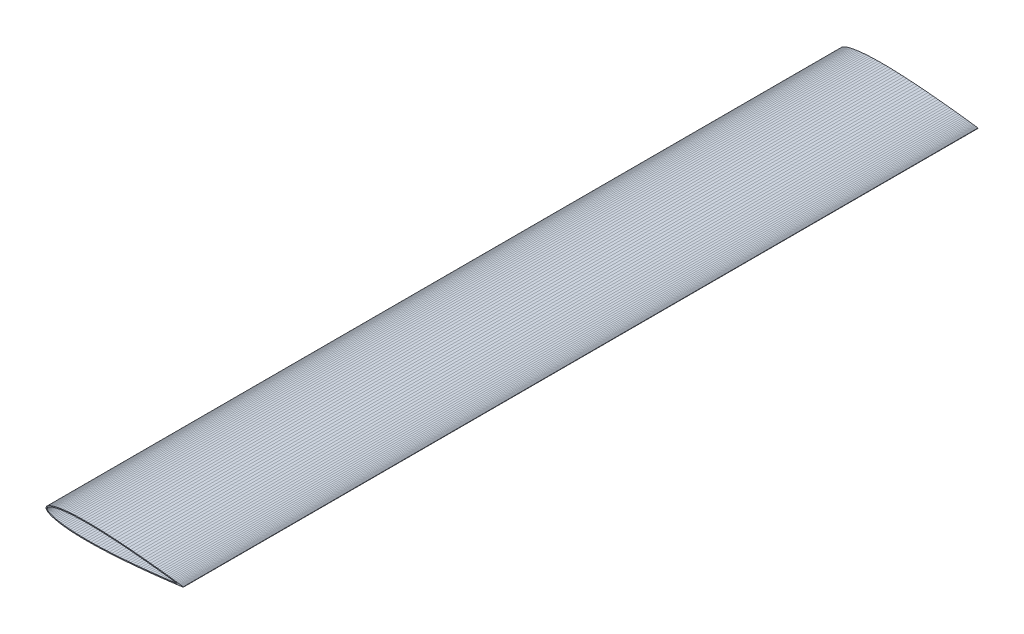
SolidWorks part; units mm, degrees
ref_plane "Front Plane" through (0, 0, 0) normal (0, 0, 1) x (1, 0, 0)
ref_plane "Top Plane" through (0, 0, 0) normal (0, 1, 0) x (1, 0, 0)
ref_plane "Right Plane" through (0, 0, 0) normal (1, 0, 0) x (0, 0, -1)
sketch "Sketch1" plane through (0, 0, 0) normal (0, 0, 1) x (1, 0, 0)
  line L0 (0.0146, 0.1318) -> (0.0586, 0.2613)
  line L1 (0.0586, 0.2613) -> (0.1317, 0.3885)
  line L2 (0.1317, 0.3885) -> (0.2339, 0.5131)
  line L3 (0.2339, 0.5131) -> (0.3651, 0.6352)
  line L4 (0.3651, 0.6352) -> (0.525, 0.7544)
  line L5 (0.525, 0.7544) -> (0.7134, 0.8708)
  line L6 (0.7134, 0.8708) -> (0.9299, 0.9839)
  line L7 (0.9299, 0.9839) -> (1.1744, 1.0938)
  line L8 (1.1744, 1.0938) -> (1.4463, 1.2)
  line L9 (1.4463, 1.2) -> (1.7453, 1.3025)
  line L10 (1.7453, 1.3025) -> (2.0709, 1.4009)
  line L11 (2.0709, 1.4009) -> (2.4226, 1.4951)
  line L12 (2.4226, 1.4951) -> (2.7998, 1.5848)
  line L13 (2.7998, 1.5848) -> (3.2021, 1.6698)
  line L14 (3.2021, 1.6698) -> (3.6287, 1.7499)
  line L15 (3.6287, 1.7499) -> (4.079, 1.8248)
  line L16 (4.079, 1.8248) -> (4.5523, 1.8944)
  line L17 (4.5523, 1.8944) -> (5.0479, 1.9586)
  line L18 (5.0479, 1.9586) -> (5.565, 2.0172)
  line L19 (5.565, 2.0172) -> (6.1028, 2.07)
  line L20 (6.1028, 2.07) -> (6.6605, 2.1169)
  line L21 (6.6605, 2.1169) -> (7.2372, 2.158)
  line L22 (7.2372, 2.158) -> (7.8321, 2.1931)
  line L23 (7.8321, 2.1931) -> (8.4442, 2.2223)
  line L24 (8.4442, 2.2223) -> (9.0725, 2.2455)
  line L25 (9.0725, 2.2455) -> (9.7162, 2.2628)
  line L26 (9.7162, 2.2628) -> (10.3742, 2.2742)
  line L27 (10.3742, 2.2742) -> (11.0455, 2.2799)
  line L28 (11.0455, 2.2799) -> (11.729, 2.28)
  line L29 (11.729, 2.28) -> (12.4238, 2.2746)
  line L30 (12.4238, 2.2746) -> (13.1287, 2.2638)
  line L31 (13.1287, 2.2638) -> (13.8426, 2.248)
  line L32 (13.8426, 2.248) -> (14.5645, 2.2272)
  line L33 (14.5645, 2.2272) -> (15.2933, 2.2016)
  line L34 (15.2933, 2.2016) -> (16.0277, 2.1716)
  line L35 (16.0277, 2.1716) -> (16.7668, 2.1374)
  line L36 (16.7668, 2.1374) -> (17.5093, 2.0991)
  line L37 (17.5093, 2.0991) -> (18.2541, 2.0572)
  line L38 (18.2541, 2.0572) -> (19, 2.0117)
  line L39 (19, 2.0117) -> (19.7459, 1.9631)
  line L40 (19.7459, 1.9631) -> (20.4907, 1.9115)
  line L41 (20.4907, 1.9115) -> (21.2332, 1.8572)
  line L42 (21.2332, 1.8572) -> (21.9723, 1.8006)
  line L43 (21.9723, 1.8006) -> (22.7067, 1.7417)
  line L44 (22.7067, 1.7417) -> (23.4355, 1.681)
  line L45 (23.4355, 1.681) -> (24.1574, 1.6186)
  line L46 (24.1574, 1.6186) -> (24.8713, 1.5549)
  line L47 (24.8713, 1.5549) -> (25.5762, 1.4899)
  line L48 (25.5762, 1.4899) -> (26.271, 1.4241)
  line L49 (26.271, 1.4241) -> (26.9545, 1.3576)
  line L50 (26.9545, 1.3576) -> (27.6258, 1.2906)
  line L51 (27.6258, 1.2906) -> (28.2838, 1.2233)
  line L52 (28.2838, 1.2233) -> (28.9275, 1.1561)
  line L53 (28.9275, 1.1561) -> (29.5558, 1.089)
  line L54 (29.5558, 1.089) -> (30.1679, 1.0224)
  line L55 (30.1679, 1.0224) -> (30.7628, 0.9564)
  line L56 (30.7628, 0.9564) -> (31.3395, 0.8912)
  line L57 (31.3395, 0.8912) -> (31.8972, 0.827)
  line L58 (31.8972, 0.827) -> (32.435, 0.7641)
  line L59 (32.435, 0.7641) -> (32.9521, 0.7026)
  line L60 (32.9521, 0.7026) -> (33.4477, 0.6427)
  line L61 (33.4477, 0.6427) -> (33.921, 0.5847)
  line L62 (33.921, 0.5847) -> (34.3713, 0.5287)
  line L63 (34.3713, 0.5287) -> (34.7979, 0.475)
  line L64 (34.7979, 0.475) -> (35.2002, 0.4237)
  line L65 (35.2002, 0.4237) -> (35.5774, 0.3749)
  line L66 (35.5774, 0.3749) -> (35.9291, 0.329)
  line L67 (35.9291, 0.329) -> (36.2547, 0.286)
  line L68 (36.2547, 0.286) -> (36.5537, 0.2462)
  line L69 (36.5537, 0.2462) -> (36.8256, 0.2096)
  line L70 (36.8256, 0.2096) -> (37.0701, 0.1764)
  line L71 (37.0701, 0.1764) -> (37.2866, 0.1468)
  line L72 (37.2866, 0.1468) -> (37.475, 0.1209)
  line L73 (37.475, 0.1209) -> (37.6349, 0.0988)
  line L74 (37.6349, 0.0988) -> (37.7661, 0.0806)
  line L75 (37.7661, 0.0806) -> (37.8683, 0.0663)
  line L76 (37.8683, 0.0663) -> (37.9414, 0.0561)
  line L77 (37.9414, 0.0561) -> (37.9854, 0.0499)
  line L78 (37.9854, 0.0499) -> (38, 0.0479)
  line L79 (38, 0.0479) -> (38, -0.0479)
  line L80 (38, -0.0479) -> (37.9854, -0.0499)
  line L81 (37.9854, -0.0499) -> (37.9414, -0.0561)
  line L82 (37.9414, -0.0561) -> (37.8683, -0.0663)
  line L83 (37.8683, -0.0663) -> (37.7661, -0.0806)
  line L84 (37.7661, -0.0806) -> (37.6349, -0.0988)
  line L85 (37.6349, -0.0988) -> (37.475, -0.1209)
  line L86 (37.475, -0.1209) -> (37.2866, -0.1468)
  line L87 (37.2866, -0.1468) -> (37.0701, -0.1764)
  line L88 (37.0701, -0.1764) -> (36.8256, -0.2096)
  line L89 (36.8256, -0.2096) -> (36.5537, -0.2462)
  line L90 (36.5537, -0.2462) -> (36.2547, -0.286)
  line L91 (36.2547, -0.286) -> (35.9291, -0.329)
  line L92 (35.9291, -0.329) -> (35.5774, -0.3749)
  line L93 (35.5774, -0.3749) -> (35.2002, -0.4237)
  line L94 (35.2002, -0.4237) -> (34.7979, -0.475)
  line L95 (34.7979, -0.475) -> (34.3713, -0.5287)
  line L96 (34.3713, -0.5287) -> (33.921, -0.5847)
  line L97 (33.921, -0.5847) -> (33.4477, -0.6427)
  line L98 (33.4477, -0.6427) -> (32.9521, -0.7026)
  line L99 (32.9521, -0.7026) -> (32.435, -0.7641)
  line L100 (32.435, -0.7641) -> (31.8972, -0.827)
  line L101 (31.8972, -0.827) -> (31.3395, -0.8912)
  line L102 (31.3395, -0.8912) -> (30.7628, -0.9564)
  line L103 (30.7628, -0.9564) -> (30.1679, -1.0224)
  line L104 (30.1679, -1.0224) -> (29.5558, -1.089)
  line L105 (29.5558, -1.089) -> (28.9275, -1.1561)
  line L106 (28.9275, -1.1561) -> (28.2838, -1.2233)
  line L107 (28.2838, -1.2233) -> (27.6258, -1.2906)
  line L108 (27.6258, -1.2906) -> (26.9545, -1.3576)
  line L109 (26.9545, -1.3576) -> (26.271, -1.4241)
  line L110 (26.271, -1.4241) -> (25.5762, -1.4899)
  line L111 (25.5762, -1.4899) -> (24.8713, -1.5549)
  line L112 (24.8713, -1.5549) -> (24.1574, -1.6186)
  line L113 (24.1574, -1.6186) -> (23.4355, -1.681)
  line L114 (23.4355, -1.681) -> (22.7067, -1.7417)
  line L115 (22.7067, -1.7417) -> (21.9723, -1.8006)
  line L116 (21.9723, -1.8006) -> (21.2332, -1.8572)
  line L117 (21.2332, -1.8572) -> (20.4907, -1.9115)
  line L118 (20.4907, -1.9115) -> (19.7459, -1.9631)
  line L119 (19.7459, -1.9631) -> (19, -2.0117)
  line L120 (19, -2.0117) -> (18.2541, -2.0572)
  line L121 (18.2541, -2.0572) -> (17.5093, -2.0991)
  line L122 (17.5093, -2.0991) -> (16.7668, -2.1374)
  line L123 (16.7668, -2.1374) -> (16.0277, -2.1716)
  line L124 (16.0277, -2.1716) -> (15.2933, -2.2016)
  line L125 (15.2933, -2.2016) -> (14.5645, -2.2272)
  line L126 (14.5645, -2.2272) -> (13.8426, -2.248)
  line L127 (13.8426, -2.248) -> (13.1287, -2.2638)
  line L128 (13.1287, -2.2638) -> (12.4238, -2.2746)
  line L129 (12.4238, -2.2746) -> (11.729, -2.28)
  line L130 (11.729, -2.28) -> (11.0455, -2.2799)
  line L131 (11.0455, -2.2799) -> (10.3742, -2.2742)
  line L132 (10.3742, -2.2742) -> (9.7162, -2.2628)
  line L133 (9.7162, -2.2628) -> (9.0725, -2.2455)
  line L134 (9.0725, -2.2455) -> (8.4442, -2.2223)
  line L135 (8.4442, -2.2223) -> (7.8321, -2.1931)
  line L136 (7.8321, -2.1931) -> (7.2372, -2.158)
  line L137 (7.2372, -2.158) -> (6.6605, -2.1169)
  line L138 (6.6605, -2.1169) -> (6.1028, -2.07)
  line L139 (6.1028, -2.07) -> (5.565, -2.0172)
  line L140 (5.565, -2.0172) -> (5.0479, -1.9586)
  line L141 (5.0479, -1.9586) -> (4.5523, -1.8944)
  line L142 (4.5523, -1.8944) -> (4.079, -1.8248)
  line L143 (4.079, -1.8248) -> (3.6287, -1.7499)
  line L144 (3.6287, -1.7499) -> (3.2021, -1.6698)
  line L145 (3.2021, -1.6698) -> (2.7998, -1.5848)
  line L146 (2.7998, -1.5848) -> (2.4226, -1.4951)
  line L147 (2.4226, -1.4951) -> (2.0709, -1.4009)
  line L148 (2.0709, -1.4009) -> (1.7453, -1.3025)
  line L149 (1.7453, -1.3025) -> (1.4463, -1.2)
  line L150 (1.4463, -1.2) -> (1.1744, -1.0938)
  line L151 (1.1744, -1.0938) -> (0.9299, -0.9839)
  line L152 (0.9299, -0.9839) -> (0.7134, -0.8708)
  line L153 (0.7134, -0.8708) -> (0.525, -0.7544)
  line L154 (0.525, -0.7544) -> (0.3651, -0.6352)
  line L155 (0.3651, -0.6352) -> (0.2339, -0.5131)
  line L156 (0.2339, -0.5131) -> (0.1317, -0.3885)
  line L157 (0.1317, -0.3885) -> (0.0586, -0.2613)
  line L158 (0.0586, -0.2613) -> (0.0146, -0.1318)
  line L159 (0.0146, -0.1318) -> (0, 0)
  line L160 (0, 0) -> (0.0146, 0.1318)
  line L161 (0.2601, -0.0772) -> (0.2875, -0.1579)
  line L162 (0.2875, -0.1579) -> (0.3381, -0.2459)
  line L163 (0.3381, -0.2459) -> (0.4166, -0.3416)
  line L164 (0.4166, -0.3416) -> (0.5254, -0.4429)
  line L165 (0.5254, -0.4429) -> (0.6657, -0.5475)
  line L166 (0.6657, -0.5475) -> (0.8371, -0.6533)
  line L167 (0.8371, -0.6533) -> (1.0391, -0.7589)
  line L168 (1.0391, -0.7589) -> (1.2711, -0.8632)
  line L169 (1.2711, -0.8632) -> (1.5323, -0.9652)
  line L170 (1.5323, -0.9652) -> (1.822, -1.0645)
  line L171 (1.822, -1.0645) -> (2.1394, -1.1605)
  line L172 (2.1394, -1.1605) -> (2.4838, -1.2527)
  line L173 (2.4838, -1.2527) -> (2.8546, -1.3409)
  line L174 (2.8546, -1.3409) -> (3.251, -1.4246)
  line L175 (3.251, -1.4246) -> (3.6723, -1.5037)
  line L176 (3.6723, -1.5037) -> (4.1177, -1.5778)
  line L177 (4.1177, -1.5778) -> (4.5865, -1.6468)
  line L178 (4.5865, -1.6468) -> (5.078, -1.7104)
  line L179 (5.078, -1.7104) -> (5.5913, -1.7685)
  line L180 (5.5913, -1.7685) -> (6.1255, -1.821)
  line L181 (6.1255, -1.821) -> (6.6799, -1.8677)
  line L182 (6.6799, -1.8677) -> (7.2535, -1.9085)
  line L183 (7.2535, -1.9085) -> (7.8454, -1.9435)
  line L184 (7.8454, -1.9435) -> (8.4547, -1.9725)
  line L185 (8.4547, -1.9725) -> (9.0805, -1.9956)
  line L186 (9.0805, -1.9956) -> (9.7217, -2.0128)
  line L187 (9.7217, -2.0128) -> (10.3774, -2.0242)
  line L188 (10.3774, -2.0242) -> (11.0465, -2.0299)
  line L189 (11.0465, -2.0299) -> (11.7281, -2.03)
  line L190 (11.7281, -2.03) -> (12.4209, -2.0246)
  line L191 (12.4209, -2.0246) -> (13.124, -2.0139)
  line L192 (13.124, -2.0139) -> (13.8363, -1.998)
  line L193 (13.8363, -1.998) -> (14.5566, -1.9773)
  line L194 (14.5566, -1.9773) -> (15.2838, -1.9518)
  line L195 (15.2838, -1.9518) -> (16.0169, -1.9219)
  line L196 (16.0169, -1.9219) -> (16.7546, -1.8877)
  line L197 (16.7546, -1.8877) -> (17.4958, -1.8495)
  line L198 (17.4958, -1.8495) -> (18.2394, -1.8076)
  line L199 (18.2394, -1.8076) -> (18.9843, -1.7622)
  line L200 (18.9843, -1.7622) -> (19.7292, -1.7136)
  line L201 (19.7292, -1.7136) -> (20.473, -1.6621)
  line L202 (20.473, -1.6621) -> (21.2145, -1.6079)
  line L203 (21.2145, -1.6079) -> (21.9527, -1.5513)
  line L204 (21.9527, -1.5513) -> (22.6864, -1.4926)
  line L205 (22.6864, -1.4926) -> (23.4143, -1.4319)
  line L206 (23.4143, -1.4319) -> (24.1355, -1.3696)
  line L207 (24.1355, -1.3696) -> (24.8487, -1.3059)
  line L208 (24.8487, -1.3059) -> (25.553, -1.241)
  line L209 (25.553, -1.241) -> (26.2471, -1.1752)
  line L210 (26.2471, -1.1752) -> (26.93, -1.1088)
  line L211 (26.93, -1.1088) -> (27.6007, -1.0418)
  line L212 (27.6007, -1.0418) -> (28.2581, -0.9747)
  line L213 (28.2581, -0.9747) -> (28.9012, -0.9075)
  line L214 (28.9012, -0.9075) -> (29.529, -0.8405)
  line L215 (29.529, -0.8405) -> (30.1406, -0.7739)
  line L216 (30.1406, -0.7739) -> (30.735, -0.7079)
  line L217 (30.735, -0.7079) -> (31.3112, -0.6428)
  line L218 (31.3112, -0.6428) -> (31.8684, -0.5787)
  line L219 (31.8684, -0.5787) -> (32.4057, -0.5158)
  line L220 (32.4057, -0.5158) -> (32.9224, -0.4544)
  line L221 (32.9224, -0.4544) -> (33.4175, -0.3946)
  line L222 (33.4175, -0.3946) -> (33.8904, -0.3366)
  line L223 (33.8904, -0.3366) -> (34.3403, -0.2807)
  line L224 (34.3403, -0.2807) -> (34.7665, -0.227)
  line L225 (34.7665, -0.227) -> (35.1683, -0.1757)
  line L226 (35.1683, -0.1757) -> (35.5452, -0.127)
  line L227 (35.5452, -0.127) -> (35.8966, -0.0811)
  line L228 (35.8966, -0.0811) -> (36.2218, -0.0382)
  line L229 (36.2218, -0.0382) -> (36.5082, 0)
  line L230 (36.5082, 0) -> (36.2218, 0.0382)
  line L231 (36.2218, 0.0382) -> (35.8966, 0.0811)
  line L232 (35.8966, 0.0811) -> (35.5452, 0.127)
  line L233 (35.5452, 0.127) -> (35.1683, 0.1757)
  line L234 (35.1683, 0.1757) -> (34.7665, 0.227)
  line L235 (34.7665, 0.227) -> (34.3403, 0.2807)
  line L236 (34.3403, 0.2807) -> (33.8904, 0.3366)
  line L237 (33.8904, 0.3366) -> (33.4175, 0.3946)
  line L238 (33.4175, 0.3946) -> (32.9224, 0.4544)
  line L239 (32.9224, 0.4544) -> (32.4057, 0.5158)
  line L240 (32.4057, 0.5158) -> (31.8684, 0.5787)
  line L241 (31.8684, 0.5787) -> (31.3112, 0.6428)
  line L242 (31.3112, 0.6428) -> (30.735, 0.7079)
  line L243 (30.735, 0.7079) -> (30.1406, 0.7739)
  line L244 (30.1406, 0.7739) -> (29.529, 0.8405)
  line L245 (29.529, 0.8405) -> (28.9012, 0.9075)
  line L246 (28.9012, 0.9075) -> (28.2581, 0.9747)
  line L247 (28.2581, 0.9747) -> (27.6007, 1.0418)
  line L248 (27.6007, 1.0418) -> (26.93, 1.1088)
  line L249 (26.93, 1.1088) -> (26.2471, 1.1752)
  line L250 (26.2471, 1.1752) -> (25.553, 1.241)
  line L251 (25.553, 1.241) -> (24.8487, 1.3059)
  line L252 (24.8487, 1.3059) -> (24.1355, 1.3696)
  line L253 (24.1355, 1.3696) -> (23.4143, 1.4319)
  line L254 (23.4143, 1.4319) -> (22.6864, 1.4926)
  line L255 (22.6864, 1.4926) -> (21.9527, 1.5513)
  line L256 (21.9527, 1.5513) -> (21.2145, 1.6079)
  line L257 (21.2145, 1.6079) -> (20.473, 1.6621)
  line L258 (20.473, 1.6621) -> (19.7292, 1.7136)
  line L259 (19.7292, 1.7136) -> (18.9843, 1.7622)
  line L260 (18.9843, 1.7622) -> (18.2394, 1.8076)
  line L261 (18.2394, 1.8076) -> (17.4958, 1.8495)
  line L262 (17.4958, 1.8495) -> (16.7546, 1.8877)
  line L263 (16.7546, 1.8877) -> (16.0169, 1.9219)
  line L264 (16.0169, 1.9219) -> (15.2838, 1.9518)
  line L265 (15.2838, 1.9518) -> (14.5566, 1.9773)
  line L266 (14.5566, 1.9773) -> (13.8363, 1.998)
  line L267 (13.8363, 1.998) -> (13.124, 2.0139)
  line L268 (13.124, 2.0139) -> (12.4209, 2.0246)
  line L269 (12.4209, 2.0246) -> (11.7281, 2.03)
  line L270 (11.7281, 2.03) -> (11.0465, 2.0299)
  line L271 (11.0465, 2.0299) -> (10.3774, 2.0242)
  line L272 (10.3774, 2.0242) -> (9.7217, 2.0128)
  line L273 (9.7217, 2.0128) -> (9.0805, 1.9956)
  line L274 (9.0805, 1.9956) -> (8.4547, 1.9725)
  line L275 (8.4547, 1.9725) -> (7.8454, 1.9435)
  line L276 (7.8454, 1.9435) -> (7.2535, 1.9085)
  line L277 (7.2535, 1.9085) -> (6.6799, 1.8677)
  line L278 (6.6799, 1.8677) -> (6.1255, 1.821)
  line L279 (6.1255, 1.821) -> (5.5913, 1.7685)
  line L280 (5.5913, 1.7685) -> (5.078, 1.7104)
  line L281 (5.078, 1.7104) -> (4.5865, 1.6468)
  line L282 (4.5865, 1.6468) -> (4.1177, 1.5778)
  line L283 (4.1177, 1.5778) -> (3.6723, 1.5037)
  line L284 (3.6723, 1.5037) -> (3.251, 1.4246)
  line L285 (3.251, 1.4246) -> (2.8546, 1.3409)
  line L286 (2.8546, 1.3409) -> (2.4838, 1.2527)
  line L287 (2.4838, 1.2527) -> (2.1394, 1.1605)
  line L288 (2.1394, 1.1605) -> (1.822, 1.0645)
  line L289 (1.822, 1.0645) -> (1.5323, 0.9652)
  line L290 (1.5323, 0.9652) -> (1.2711, 0.8632)
  line L291 (1.2711, 0.8632) -> (1.0391, 0.7589)
  line L292 (1.0391, 0.7589) -> (0.8371, 0.6533)
  line L293 (0.8371, 0.6533) -> (0.6657, 0.5475)
  line L294 (0.6657, 0.5475) -> (0.5254, 0.4429)
  line L295 (0.5254, 0.4429) -> (0.4166, 0.3416)
  line L296 (0.4166, 0.3416) -> (0.3381, 0.2459)
  line L297 (0.3381, 0.2459) -> (0.2875, 0.1579)
  line L298 (0.2875, 0.1579) -> (0.2601, 0.0772)
  line L299 (0.2601, 0.0772) -> (0.2515, 0)
  line L300 (0.2515, 0) -> (0.2601, -0.0772)
extrude "Defined_Material_Section_L220" add sketch "Sketch1" along normal blind 220
